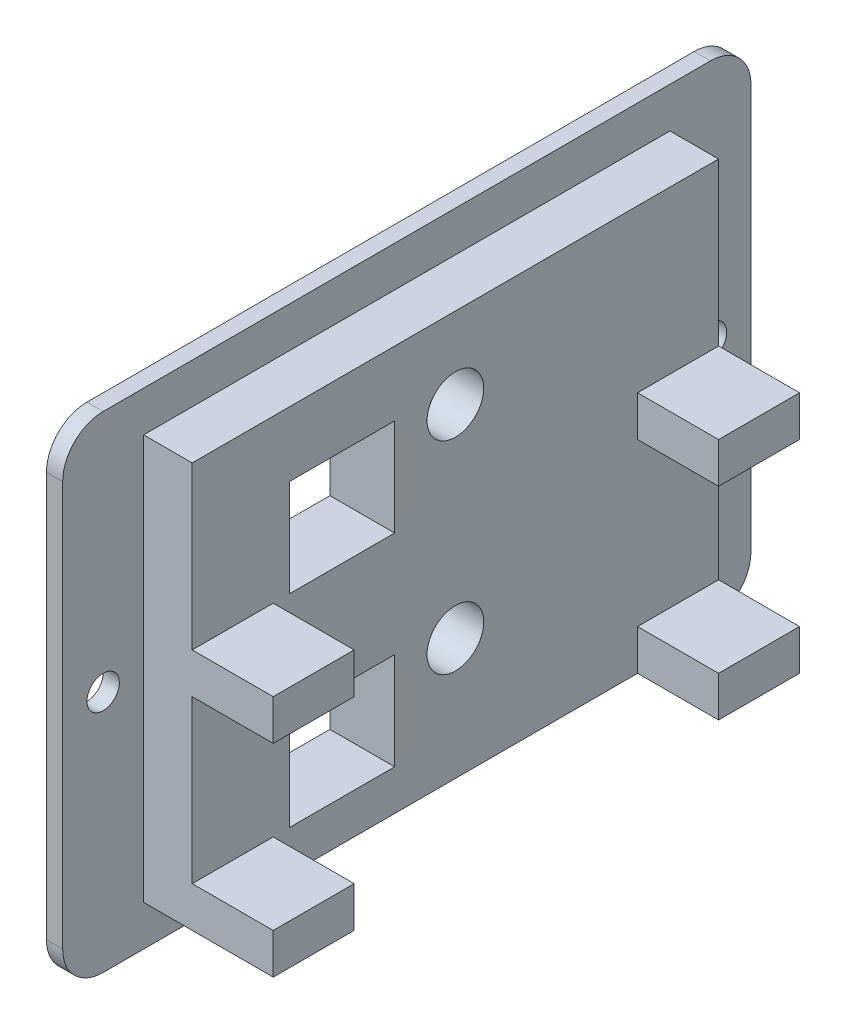
SolidWorks part; units mm, degrees
ref_plane "Front Plane" through (0, 0, 0) normal (0, 0, 1) x (1, 0, 0)
ref_plane "Top Plane" through (0, 0, 0) normal (0, 1, 0) x (1, 0, 0)
ref_plane "Right Plane" through (0, 0, 0) normal (1, 0, 0) x (0, 0, -1)
sketch "Sketch1" plane through (0, 0, 0) normal (1, 0, 0) x (0, 0, -1)
  line L1 (0, 0) -> (85, 0)
  line L2 (0, 0) -> (0, 60)
  line L3 (0, 60) -> (85, 60)
  line L4 (85, 0) -> (85, 60)
  dimension "D1" = 60
  dimension "D2" = 85
extrude "Boss-Extrude1" add sketch "Sketch1" along normal blind 1
sketch "Sketch2" plane through (1, 0, 0) normal (1, 0, 0) x (0, 0, -1)
  line L0 (0, 0) -> (85, 0) construction
  line L1 (10, 55) -> (75, 55)
  line L2 (10, 55) -> (10, 5)
  line L3 (10, 5) -> (75, 5)
  line L4 (75, 55) -> (75, 5)
  line L5 (85, 60) -> (0, 60) construction
  line L6 (85, 0) -> (85, 60) construction
  line L7 (0, 60) -> (0, 0) construction
  dimension "D1" = 5
  dimension "D2" = 5
  dimension "D3" = 10
  dimension "D4" = 10
extrude "Boss-Extrude2" add sketch "Sketch2" along normal blind 6
sketch "Sketch3" plane through (7, 0, 0) normal (1, 0, 0) x (0, 0, -1)
  line L0 (10, 55) -> (10, 5) construction
  line L1 (10, 5) -> (20, 5)
  line L2 (10, 5) -> (10, 10)
  line L3 (10, 10) -> (20, 10)
  line L4 (20, 5) -> (20, 10)
  line L5 (75, 5) -> (65, 5)
  line L6 (75, 5) -> (75, 10)
  line L7 (75, 10) -> (65, 10)
  line L8 (65, 5) -> (65, 10)
  line L9 (10, 30) -> (20, 30)
  line L10 (10, 30) -> (10, 35)
  line L11 (10, 35) -> (20, 35)
  line L12 (20, 30) -> (20, 35)
  line L13 (75, 5) -> (75, 55) construction
  line L14 (75, 30) -> (65, 30)
  line L15 (75, 30) -> (75, 35)
  line L16 (75, 35) -> (65, 35)
  line L17 (65, 30) -> (65, 35)
  point P5 (15, 10)
  dimension "D1" = 5
  dimension "D2" = 5
  dimension "D3" = 10
  dimension "D4" = 5
extrude "Boss-Extrude3" add sketch "Sketch3" along normal blind 10
sketch "Sketch4" plane through (1, 0, 0) normal (1, 0, 0) x (0, 0, -1)
  line L0 (0, 60) -> (0, 0) construction
  line L1 (85, 0) -> (85, 60) construction
  circle A0 centre (5, 30) radius 2
  circle A1 centre (80, 30) radius 2
  point P6 (0, 30)
  point P9 (85, 30)
  dimension "D3" = 4
  dimension "D4" = 4
  dimension "D1" = 5
  dimension "D2" = 5
extrude "Cut-Extrude1" cut sketch "Sketch4" against normal blind 10
sketch "Sketch5" plane through (0, 0, 0) normal (-1, 0, 0) x (0, 0, 1)
  line L1 (-85, 60) -> (0, 60)
  line L2 (-85, 60) -> (-85, 0)
  line L3 (-85, 0) -> (0, 0)
  line L4 (0, 60) -> (0, 0)
  circle A0 centre (-80, 30) radius 2
  circle A1 centre (-5, 30) radius 2
extrude "Boss-Extrude4" add sketch "Sketch5" along normal blind 1
sketch "Sketch6" plane through (-1, 0, 0) normal (-1, 0, 0) x (0, 0, 1)
  line L0 (0, 0) -> (0, 60) construction
  line L1 (-35, 35) -> (-22, 35)
  line L2 (-35, 35) -> (-35, 47)
  line L3 (-35, 47) -> (-22, 47)
  line L4 (-22, 35) -> (-22, 47)
  line L5 (-20, 10) -> (-10, 10) construction
  line L6 (-22, 10) -> (-35, 10)
  line L7 (-22, 10) -> (-22, 22)
  line L8 (-22, 22) -> (-35, 22)
  line L9 (-35, 10) -> (-35, 22)
  circle A0 centre (-42.5, 45) radius 3.5
  circle A1 centre (-42.5, 20) radius 3.5
  point P4 (-28.5, 47)
  point P5 (-28.5, 35)
  dimension "D5" = 7
  dimension "D8" = 7
  dimension "D1" = 12
  dimension "D2" = 6.5
  dimension "D3" = 28.5
  dimension "D4" = 12
  dimension "D6" = 10
  dimension "D7" = 42.5
  dimension "D9" = 10
extrude "Cut-Extrude2" cut sketch "Sketch6" against normal blind 10 contours L8 L9 L6 L7 | L2 L3 L4 L1 | A0 | A1
fillet "Fillet1" radius 5 1 edges at (0, 60, 0)
fillet "Fillet2" radius 5 1 edges at (0, 0, 0)
fillet "Fillet3" radius 5 1 edges at (0, 60, -85)
fillet "Fillet4" radius 5 1 edges at (0, 0, -85)
